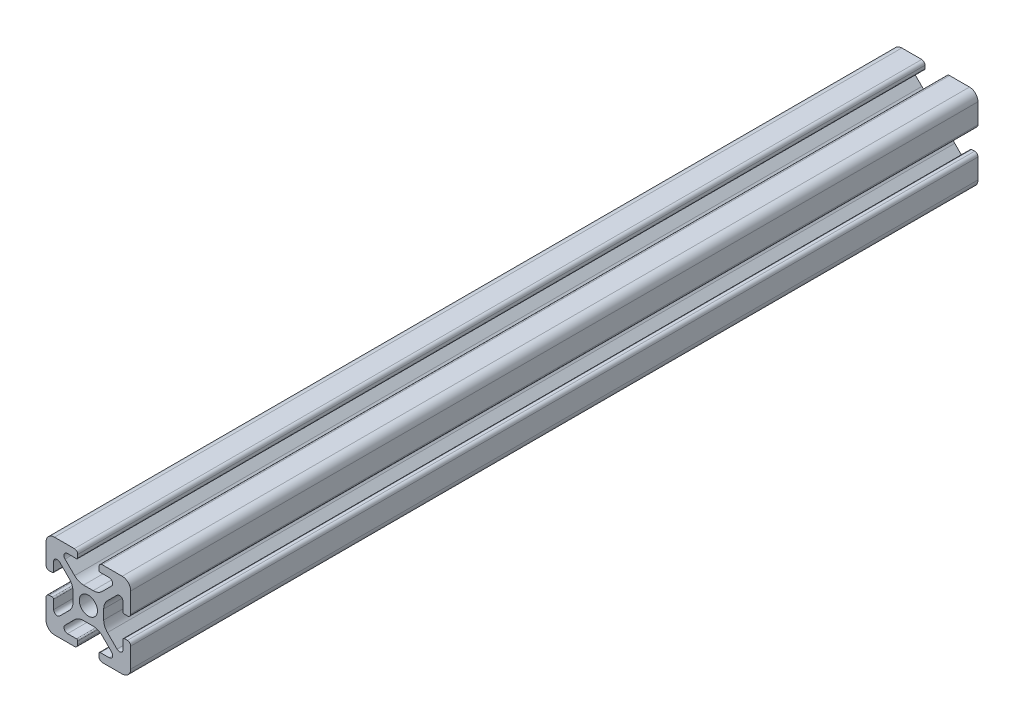
SolidWorks part; units mm, degrees
ref_plane "Front Plane" through (0, 0, 0) normal (0, 0, 1) x (1, 0, 0)
ref_plane "Top Plane" through (0, 0, 0) normal (0, 1, 0) x (1, 0, 0)
ref_plane "Right Plane" through (0, 0, 0) normal (1, 0, 0) x (0, 0, -1)
sketch "Sketch1" plane through (0, 0, 0) normal (0, 0, 1) x (1, 0, 0)
  line L2 (-9.9949, 7.9883) -> (-9.9949, 3.2893)
  line L3 (-7.9883, 9.9949) -> (-3.2893, 9.9949)
  line L4 (-2.5019, 9.2075) -> (-2.5019, 8.4963)
  line L5 (-2.8067, 8.1915) -> (-4.9149, 8.1915)
  line L6 (-5.5076, 6.7606) -> (-3.2528, 4.5058)
  line L7 (-6.7606, 5.5076) -> (-4.5058, 3.2528)
  line L8 (-8.1915, 4.9149) -> (-8.1915, 2.8067)
  line L9 (-8.4963, 2.5019) -> (-9.2075, 2.5019)
  line L11 (-1.1334, 3.6279) -> (1.1334, 3.6279)
  line L12 (-3.6279, 1.1334) -> (-3.6279, -1.1334)
  line L13 (8.4963, 2.5019) -> (9.2075, 2.5019)
  line L14 (8.1915, 4.9149) -> (8.1915, 2.8067)
  line L15 (9.9949, 7.9883) -> (9.9949, 3.2893)
  line L16 (7.9883, 9.9949) -> (3.2893, 9.9949)
  line L17 (2.5019, 9.2075) -> (2.5019, 8.4963)
  line L18 (2.8067, 8.1915) -> (4.9149, 8.1915)
  line L19 (3.6279, 1.1334) -> (3.6279, -1.1334)
  line L20 (5.5076, 6.7606) -> (3.2528, 4.5058)
  line L21 (6.7606, 5.5076) -> (4.5058, 3.2528)
  line L22 (-8.4963, -2.5019) -> (-9.2075, -2.5019)
  line L23 (-8.1915, -4.9149) -> (-8.1915, -2.8067)
  line L24 (-6.7606, -5.5076) -> (-4.5058, -3.2528)
  line L25 (-5.5076, -6.7606) -> (-3.2528, -4.5058)
  line L26 (-2.8067, -8.1915) -> (-4.9149, -8.1915)
  line L27 (-2.5019, -9.2075) -> (-2.5019, -8.4963)
  line L28 (-7.9883, -9.9949) -> (-3.2893, -9.9949)
  line L29 (-9.9949, -7.9883) -> (-9.9949, -3.2893)
  line L30 (9.9949, -7.9883) -> (9.9949, -3.2893)
  line L31 (7.9883, -9.9949) -> (3.2893, -9.9949)
  line L32 (2.5019, -9.2075) -> (2.5019, -8.4963)
  line L33 (2.8067, -8.1915) -> (4.9149, -8.1915)
  line L34 (5.5076, -6.7606) -> (3.2528, -4.5058)
  line L35 (6.7606, -5.5076) -> (4.5058, -3.2528)
  line L36 (8.1915, -4.9149) -> (8.1915, -2.8067)
  line L37 (8.4963, -2.5019) -> (9.2075, -2.5019)
  line L38 (-1.1334, -3.6279) -> (1.1334, -3.6279)
  circle A0 centre (0, 0) radius 2.1463
  arc A1 (-9.9949, 7.9883) -> (-7.9883, 9.9949) centre (-7.9883, 7.9883) cw
  arc A2 (-6.7606, 5.5076) -> (-8.1915, 4.9149) centre (-7.3533, 4.9149) ccw
  arc A3 (-4.9149, 8.1915) -> (-5.5076, 6.7606) centre (-4.9149, 7.3533) ccw
  arc A4 (-3.2893, 9.9949) -> (-2.5019, 9.2075) centre (-3.2893, 9.2075) cw
  arc A5 (-9.9949, 3.2893) -> (-9.2075, 2.5019) centre (-9.2075, 3.2893) ccw
  arc A6 (-8.1915, 2.8067) -> (-8.4963, 2.5019) centre (-8.4963, 2.8067) cw
  arc A7 (-2.5019, 8.4963) -> (-2.8067, 8.1915) centre (-2.8067, 8.4963) cw
  arc A8 (-1.1334, 3.6279) -> (-3.2528, 4.5058) centre (-1.1334, 6.6251) cw
  arc A9 (-3.6279, 1.1334) -> (-4.5058, 3.2528) centre (-6.6251, 1.1334) ccw
  arc A10 (8.1915, 2.8067) -> (8.4963, 2.5019) centre (8.4963, 2.8067) ccw
  arc A11 (9.9949, 3.2893) -> (9.2075, 2.5019) centre (9.2075, 3.2893) cw
  arc A12 (9.9949, 7.9883) -> (7.9883, 9.9949) centre (7.9883, 7.9883) ccw
  arc A13 (3.2893, 9.9949) -> (2.5019, 9.2075) centre (3.2893, 9.2075) ccw
  arc A14 (2.5019, 8.4963) -> (2.8067, 8.1915) centre (2.8067, 8.4963) ccw
  arc A15 (1.1334, 3.6279) -> (3.2528, 4.5058) centre (1.1334, 6.6251) ccw
  arc A16 (3.6279, 1.1334) -> (4.5058, 3.2528) centre (6.6251, 1.1334) cw
  arc A17 (6.7606, 5.5076) -> (8.1915, 4.9149) centre (7.3533, 4.9149) cw
  arc A18 (4.9149, 8.1915) -> (5.5076, 6.7606) centre (4.9149, 7.3533) cw
  arc A19 (-3.6279, -1.1334) -> (-4.5058, -3.2528) centre (-6.6251, -1.1334) cw
  arc A20 (-1.1334, -3.6279) -> (-3.2528, -4.5058) centre (-1.1334, -6.6251) ccw
  arc A21 (-2.5019, -8.4963) -> (-2.8067, -8.1915) centre (-2.8067, -8.4963) ccw
  arc A22 (-8.1915, -2.8067) -> (-8.4963, -2.5019) centre (-8.4963, -2.8067) ccw
  arc A23 (-9.9949, -3.2893) -> (-9.2075, -2.5019) centre (-9.2075, -3.2893) cw
  arc A24 (-3.2893, -9.9949) -> (-2.5019, -9.2075) centre (-3.2893, -9.2075) ccw
  arc A25 (-4.9149, -8.1915) -> (-5.5076, -6.7606) centre (-4.9149, -7.3533) cw
  arc A26 (-6.7606, -5.5076) -> (-8.1915, -4.9149) centre (-7.3533, -4.9149) cw
  arc A27 (-9.9949, -7.9883) -> (-7.9883, -9.9949) centre (-7.9883, -7.9883) ccw
  arc A28 (9.9949, -7.9883) -> (7.9883, -9.9949) centre (7.9883, -7.9883) cw
  arc A29 (6.7606, -5.5076) -> (8.1915, -4.9149) centre (7.3533, -4.9149) ccw
  arc A30 (4.9149, -8.1915) -> (5.5076, -6.7606) centre (4.9149, -7.3533) ccw
  arc A31 (3.2893, -9.9949) -> (2.5019, -9.2075) centre (3.2893, -9.2075) cw
  arc A32 (9.9949, -3.2893) -> (9.2075, -2.5019) centre (9.2075, -3.2893) ccw
  arc A33 (8.1915, -2.8067) -> (8.4963, -2.5019) centre (8.4963, -2.8067) cw
  arc A34 (2.5019, -8.4963) -> (2.8067, -8.1915) centre (2.8067, -8.4963) cw
  arc A35 (1.1334, -3.6279) -> (3.2528, -4.5058) centre (1.1334, -6.6251) cw
  arc A36 (3.6279, -1.1334) -> (4.5058, -3.2528) centre (6.6251, -1.1334) ccw
extrude "Boss-Extrude1" add sketch "Sketch1" along normal mid plane 200
hole_wizard "M6 Clearance Hole1" positions "Sketch2" profile "Sketch3" hole size "M6" standard "ANSI Metric"
sketch "Sketch2" plane through (0, 3.6279, 0) normal (0, 1, 0) x (-1, 0, 0)
  line L0 (-1.1334, 100) -> (1.1334, 100) construction
  point P0 (0, 87.6379)
  point P3 (0, -82.3621)
  dimension "D1" = 12.3621
  dimension "D2" = 170
sketch "Sketch3" plane through (0, 3.6279, 87.6379) normal (1, 0, 0) x (0, 0, 1)
  line L0 (0, 0) -> (0, 29.863)
  line L1 (0, 29.863) -> (3.5, 27.76)
  line L2 (3.5, 27.76) -> (3.5, 0)
  line L5 (3.5, 0) -> (0, 0)
  line L10 (0, 29.863) -> (-3.5, 27.76) construction
  line L11 (0, -6.35) -> (0, 107.95) construction
  dimension "Hole Dia." = 7
  dimension "Hole Depth" = 27.76
  dimension "Drill Angle" = 118
